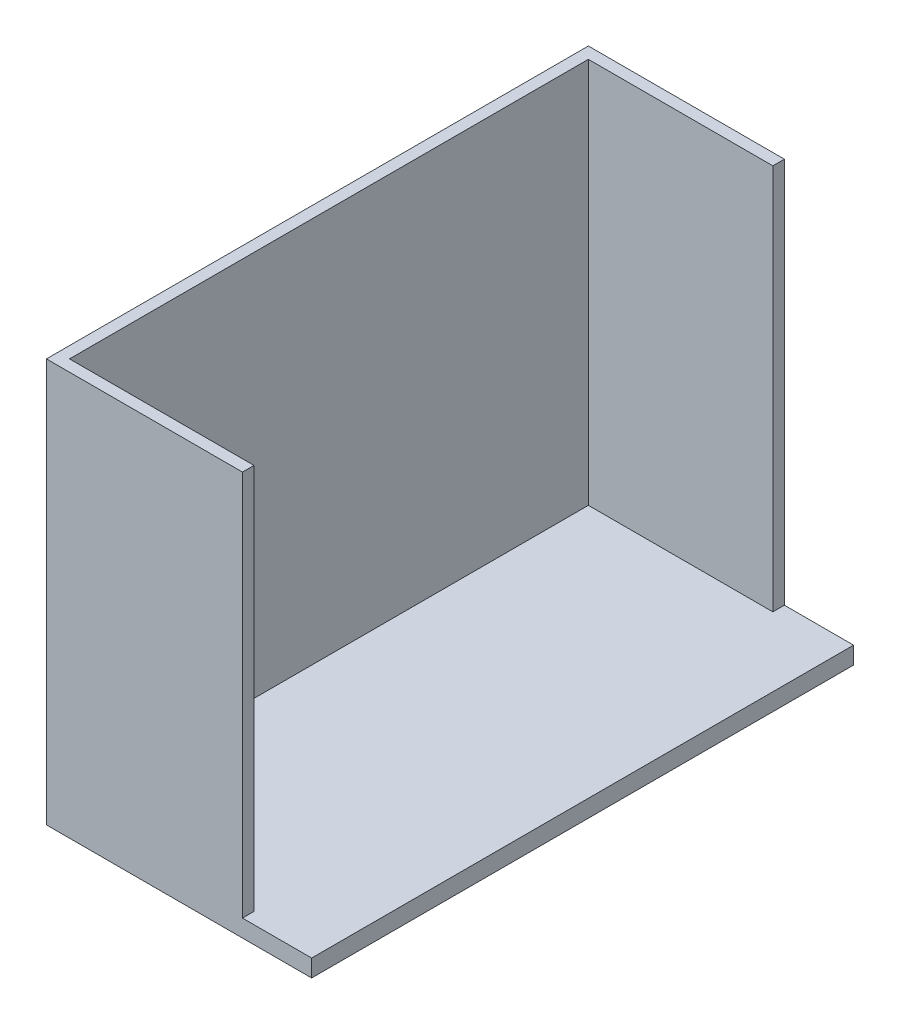
SolidWorks part; units mm, degrees
ref_plane "Front Plane" through (0, 0, 0) normal (0, 0, 1) x (1, 0, 0)
ref_plane "Top Plane" through (0, 0, 0) normal (0, 1, 0) x (1, 0, 0)
ref_plane "Right Plane" through (0, 0, 0) normal (1, 0, 0) x (0, 0, -1)
sketch "Sketch1" plane through (0, 0, 0) normal (0, 1, 0) x (1, 0, 0)
  line L1 (-146.05, -298.45) -> (146.05, -298.45)
  line L2 (-146.05, -298.45) -> (-146.05, 298.45)
  line L3 (-146.05, 298.45) -> (146.05, 298.45)
  line L4 (146.05, -298.45) -> (146.05, 298.45)
  line L5 (-146.05, -298.45) -> (146.05, 298.45) construction
  line L6 (-146.05, 298.45) -> (146.05, -298.45) construction
  point P0 (0, 0)
  dimension "D1" = 596.9
  dimension "D2" = 292.1
extrude "Boss-Extrude1" add sketch "Sketch1" along normal blind 19.05
sketch "Sketch2" plane through (0, 19.05, 0) normal (0, 1, 0) x (1, 0, 0)
  line L0 (-146.05, -298.45) -> (-146.05, 298.45)
  line L1 (-146.05, 298.45) -> (-146.05, -298.45) construction
  line L2 (-146.05, -298.45) -> (146.05, -298.45) construction
  line L5 (-146.05, 298.45) -> (69.85, 298.45)
  line L6 (-146.05, -298.45) -> (69.85, -298.45)
  line L7 (69.85, -298.45) -> (69.85, -285.75)
  line L8 (69.85, 285.75) -> (-133.35, 285.75)
  line L9 (-133.35, 285.75) -> (-133.35, -285.75)
  line L11 (69.85, -285.75) -> (-133.35, -285.75)
  line L12 (69.85, 298.45) -> (69.85, 285.75)
  point P5 (139.7707, 285.75)
  point P8 (69.85, 285.75)
  point P11 (0, 0)
  point P13 (0, 0)
  point P15 (146.05, -298.45)
  dimension "D1" = 12.7
  dimension "D2" = 12.7
  dimension "D3" = 12.7
  dimension "D4" = 76.2
extrude "Boss-Extrude2" add sketch "Sketch2" along normal blind 425.45
